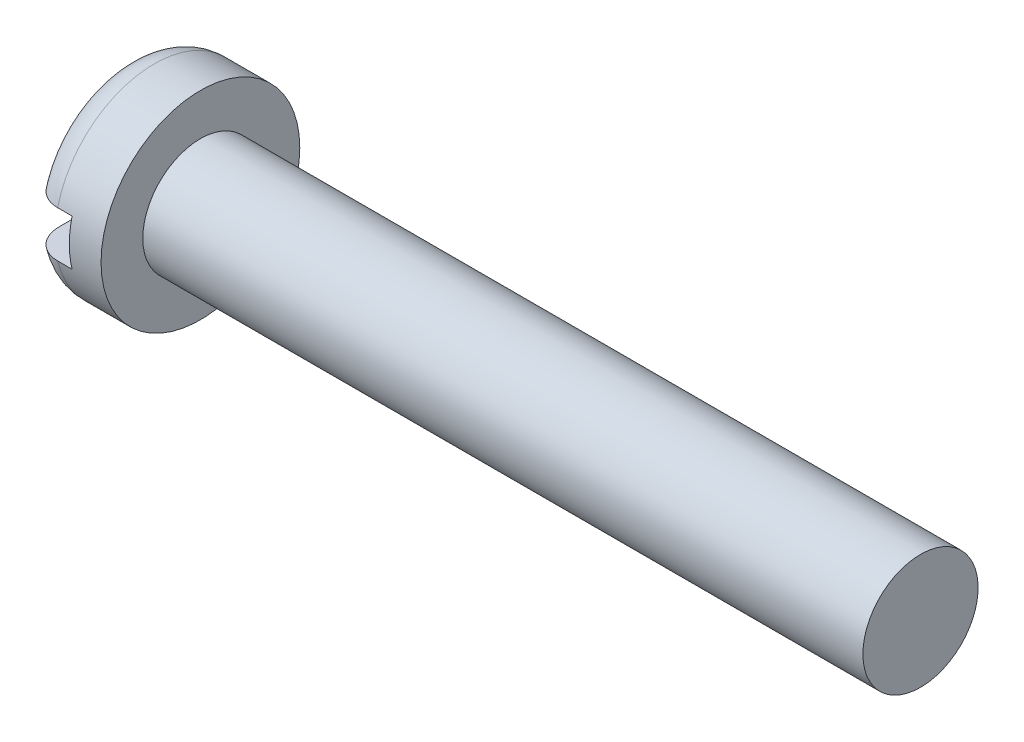
SolidWorks part; units mm, degrees
ref_plane "Plane1" through (0, 0, 0) normal (0, 0, 1) x (1, 0, 0)
ref_plane "Plane2" through (0, 0, 0) normal (0, 1, 0) x (1, 0, 0)
ref_plane "Plane3" through (0, 0, 0) normal (1, 0, 0) x (0, 0, -1)
sketch "BodySke" plane through (0, 0, 0) normal (0, 0, 1) x (1, 0, 0)
  line L0 (2.6, 2) -> (2.6, 3.45)
  line L1 (0, 0) -> (0, 2.45)
  line L2 (-25.4, 0) -> (127, 0) construction
  line L3 (27.6, 0) -> (0, 0)
  line L4 (2.6, 2) -> (27.6, 2)
  line L5 (27.6, 2) -> (27.6, 0)
  line L6 (1, 3.45) -> (2.6, 3.45)
  line L7 (2.6, -2) -> (27.6, -2) construction
  line L8 (0, -3.45) -> (2.6, -3.45) construction
  line L9 (4.1, 3.5875) -> (4.1, -5.9375) construction
  line L10 (2.6, 6.35) -> (2.6, -3.175) construction
  arc A0 (0, 2.45) -> (1, 3.45) centre (1, 2.45) cw
  point P15 (0, 3.45)
  dimension "Head_fillet_rad" = 1
  dimension "Diameter" = 4
  dimension "Length" = 25
  dimension "Head_ht" = 2.6
  dimension "Head_dia" = 6.9
  dimension "Advance" = 1.5
  dimension "Thread_nom" = 25
revolve "Base-Revolve" add sketch "BodySke" angle 360 about L2
cosmetic thread "ThreadCosmetic" [suppressed] parameters "Thread_length"=23.5, "Thread_minor"=8.344
sketch "Sketch2" plane through (0, 0, 0) normal (1, 0, 0) x (0, 0, -1)
  line L0 (3.45, -0.8) -> (-3.45, -0.8)
  line L1 (3.45, -0.8) -> (3.45, 0.8)
  line L2 (-3.45, 0.8) -> (3.45, 0.8)
  line L3 (-3.45, 0.8) -> (-3.45, -0.8)
  dimension "D1" = 6.9
  dimension "Slot_width" = 1.6
  dimension "D2" = 3.45
  dimension "D3" = 0.8
extrude "Slot" cut sketch "Sketch2" along normal blind 1.5
sketch "ThdSchSke" plane through (0, 0, 0) normal (0, 0, 1) x (1, 0, 0)
  line L0 (4.1, -4.172) -> (5.6209, -2)
  line L1 (4.1, -4.172) -> (2.5791, -2)
  line L2 (2.5791, -2) -> (2.5791, -2.5)
  line L3 (-3.175, 0) -> (5.1513, 0) construction
  line L5 (2.5791, -2.5) -> (5.6209, -2.5)
  line L6 (5.6209, -2.5) -> (5.6209, -2)
  dimension "Diameter" = 4
  dimension "SideAngle" = 55
  dimension "VeeAngle" = 70
  dimension "Thread_minor" = 8.344
  dimension "Overcut" = 5
  dimension "Start" = 4.1
revolve "ThreadSchematic" [suppressed] cut sketch "ThdSchSke" angle 360 about L3
pattern_linear "ThdSchPat" [suppressed]
equation "\"D1@Sketch2\" = \"Head_dia@BodySke\""
equation "\"D2@Sketch2\" = \"D1@Sketch2\" / 2"
equation "\"D3@Sketch2\" = \"Slot_width@Sketch2\" / 2"
equation "\"Thread_length@ThreadCosmetic\" = ((sgn( (\"Length@BodySke\" - \"Advance@BodySke\" ) - \"Thread_nom@BodySke\" )-1)*( (\"Length@BodySke\" - \"Advance@BodySke\" ) - \"Thread_nom@BodySke\" ))/-2+ \"Thread_nom@BodySke\""
equation "\"Thread_minor@ThdSchSke\" = \"Thread_minor@ThreadCosmetic\""
equation "\"Diameter@ThdSchSke\" = \"Diameter@BodySke\""
equation "\"Overcut@ThdSchSke\" = \"Diameter@BodySke\" * 1.25"
equation "\"Start@ThdSchSke\" = \"Head_ht@BodySke\" + \"Length@BodySke\" - \"Thread_length@ThreadCosmetic\"  '---Non-countersunk---"
equation "\"Num_threads@ThdSchPat\" = int( \"Thread_length@ThreadCosmetic\" / \"Advance@BodySke\" + 0.999 )  + 1"
equation "\"Advance@ThdSchPat\" = \"Thread_length@ThreadCosmetic\" /  (\"Num_threads@ThdSchPat\" - 1) 'relax it"
